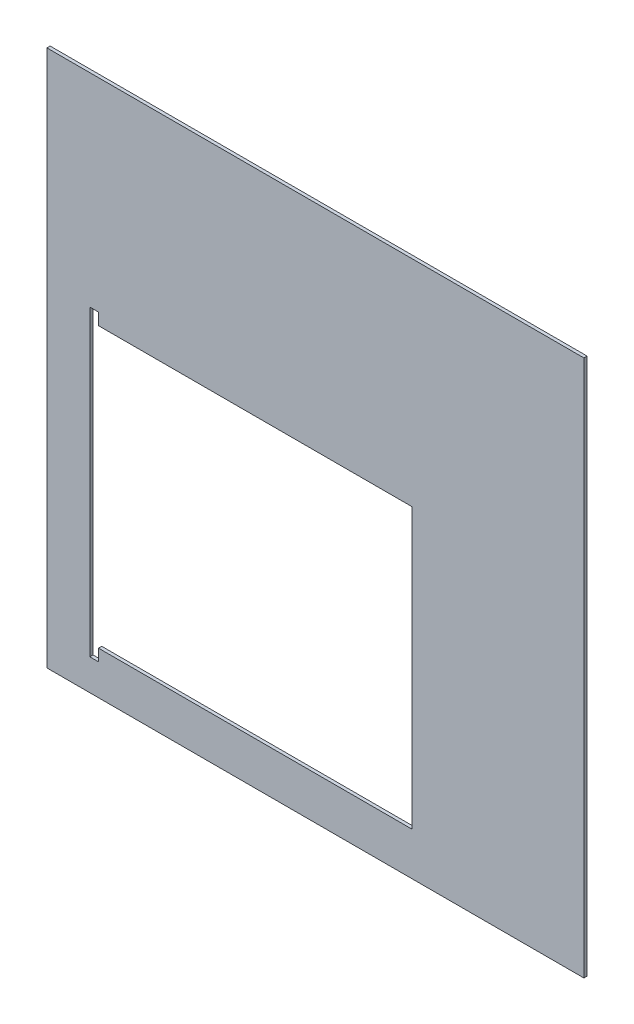
SolidWorks part; units mm, degrees
ref_plane "Plan de face" through (0, 0, 0) normal (0, 0, 1) x (1, 0, 0)
ref_plane "Plan de dessus" through (0, 0, 0) normal (0, 1, 0) x (1, 0, 0)
ref_plane "Plan de droite" through (0, 0, 0) normal (1, 0, 0) x (0, 0, -1)
sketch "Esquisse1" plane through (0, 0, 0) normal (0, 0, 1) x (1, 0, 0)
  line L0 (20, 85) -> (170, 85) construction
  line L1 (0, 0) -> (250, 0)
  line L2 (0, 0) -> (0, 250)
  line L3 (0, 250) -> (250, 250)
  line L4 (250, 0) -> (250, 250)
  line L5 (24, 20) -> (170, 20)
  line L6 (20, 20) -> (20, 150)
  line L7 (24, 150) -> (170, 150)
  line L8 (170, 20) -> (170, 150)
  line L10 (20, 150) -> (20, 155.5)
  line L11 (20, 155.5) -> (24, 155.5)
  line L12 (24, 150) -> (24, 155.5)
  line L13 (20, 20) -> (20, 14.5)
  line L14 (20, 14.5) -> (24, 14.5)
  line L15 (24, 20) -> (24, 14.5)
  dimension "D1" = 250
  dimension "D2" = 250
  dimension "D3" = 150
  dimension "D4" = 130
  dimension "D5" = 20
  dimension "D6" = 80
  dimension "D7" = 4
  dimension "D8" = 5.5
extrude "Boss.-Extru.1" add sketch "Esquisse1" along normal blind 1.5
